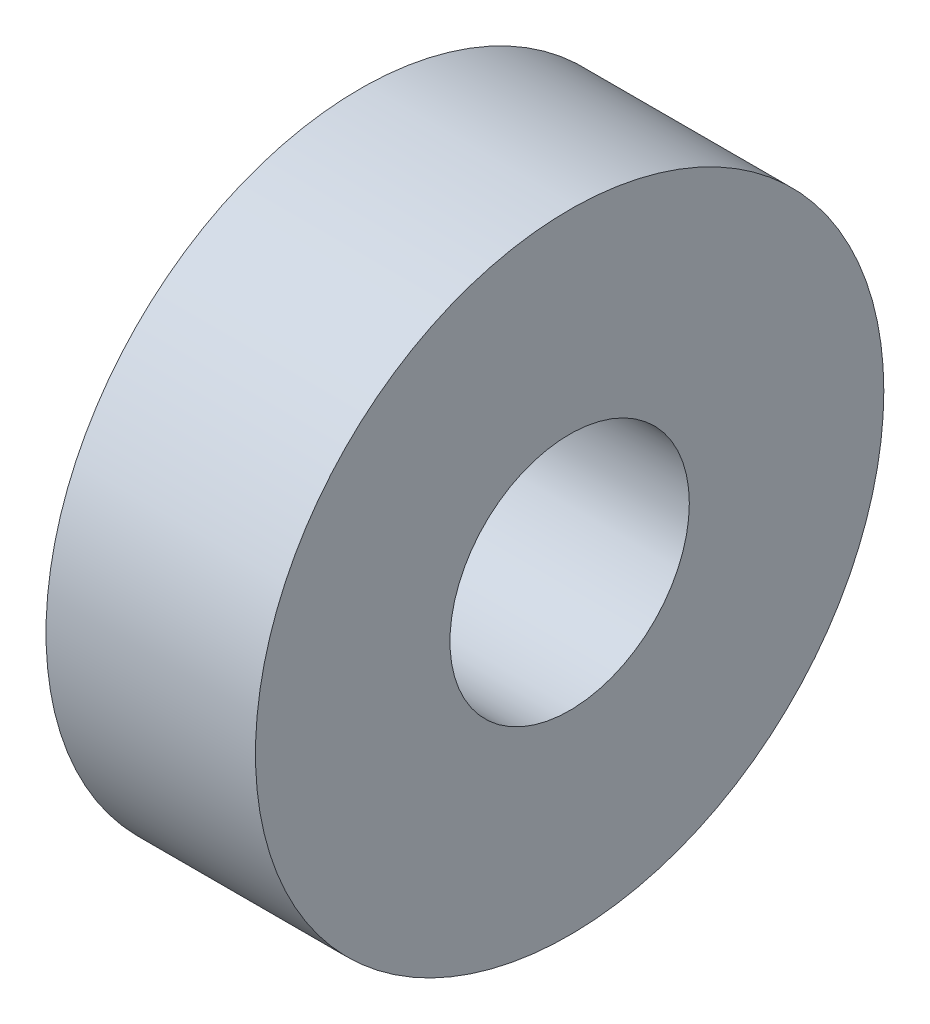
SolidWorks part; units mm, degrees
ref_plane "Plano frontal" through (0, 0, 0) normal (0, 0, 1) x (1, 0, 0)
ref_plane "Plano superior" through (0, 0, 0) normal (0, 1, 0) x (1, 0, 0)
ref_plane "Plano direito" through (0, 0, 0) normal (1, 0, 0) x (0, 0, -1)
sketch "Esboço1" plane through (0, 0, 0) normal (1, 0, 0) x (0, 0, -1)
  circle A0 centre (0, 0) radius 10.5
  circle A1 centre (0, 0) radius 4
  dimension "D1" = 21
  dimension "D2" = 8
extrude "Ressalto-extrusão1" add sketch "Esboço1" along normal blind 7 contours A0 | A1
